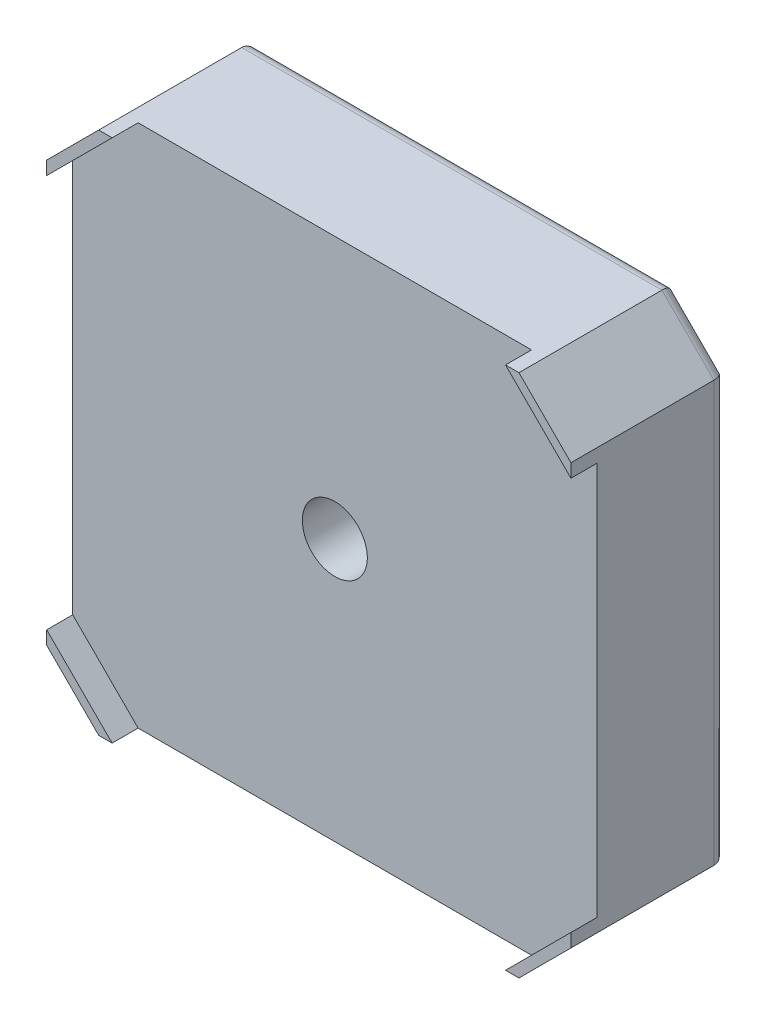
SolidWorks part; units mm, degrees
ref_plane "Front Plane" through (0, 0, 0) normal (0, 0, 1) x (1, 0, 0)
ref_plane "Top Plane" through (0, 0, 0) normal (0, 1, 0) x (1, 0, 0)
ref_plane "Right Plane" through (0, 0, 0) normal (1, 0, 0) x (0, 0, -1)
sketch "Sketch1" plane through (0, 0, 0) normal (0, 0, 1) x (1, 0, 0)
  line L0 (-48.5, 60.5) -> (-60.5, 48.5)
  line L1 (48.5, -60.5) -> (-48.5, -60.5)
  line L2 (60.5, -48.5) -> (60.5, 48.5)
  line L3 (48.5, 60.5) -> (-48.5, 60.5)
  line L4 (-60.5, -48.5) -> (-60.5, 48.5)
  line L5 (60.5, -60.5) -> (-60.5, 60.5) construction
  line L6 (60.5, 60.5) -> (-60.5, -60.5) construction
  line L7 (60.5, 48.5) -> (48.5, 60.5)
  line L8 (60.5, -48.5) -> (48.5, -60.5)
  line L9 (-48.5, -60.5) -> (-60.5, -48.5)
  point P0 (0, 0)
  dimension "D1" = 121
  dimension "D2" = 121
extrude "Boss-Extrude1" add sketch "Sketch1" along normal blind 36
sketch "Sketch2" plane through (0, 0, 36) normal (0, 0, 1) x (1, 0, 0)
  line L0 (-42.45, 63.45) -> (-63.45, 42.45)
  line L1 (42.45, -63.45) -> (-42.45, -63.45)
  line L2 (63.45, -42.45) -> (63.45, 42.45)
  line L3 (42.45, 63.45) -> (-42.45, 63.45)
  line L4 (-63.45, -42.45) -> (-63.45, 42.45)
  line L5 (63.45, -63.45) -> (-63.45, 63.45) construction
  line L6 (63.45, 63.45) -> (-63.45, -63.45) construction
  line L7 (63.45, 42.45) -> (42.45, 63.45)
  line L8 (63.45, -42.45) -> (42.45, -63.45)
  line L9 (-42.45, -63.45) -> (-63.45, -42.45)
  point P0 (0, 0)
  dimension "D1" = 126.9
  dimension "D2" = 126.9
extrude "Cut-Extrude1" cut sketch "Sketch2" against normal blind 6
sketch "Sketch3" plane through (0, 0, 0) normal (0, 0, -1) x (-1, 0, 0)
  circle A0 centre (0, 0) radius 33
  dimension "D1" = 66
extrude "Boss-Extrude2" add sketch "Sketch3" along normal blind 6
sketch "Sketch4" plane through (0, 0, -6) normal (0, 0, -1) x (-1, 0, 0)
  circle A0 centre (0, 0) radius 16.5
  dimension "D1" = 33
extrude "Cut-Extrude2" cut sketch "Sketch4" against normal blind 21
sketch "Sketch5" plane through (0, 0, 15) normal (0, 0, -1) x (-1, 0, 0)
  circle A0 centre (0, 0) radius 7.5
  dimension "D1" = 15
extrude "Cut-Extrude3" cut sketch "Sketch5" against normal through all
fillet "Fillet1" radius 3 8 edges at (-54.5, 54.5, 0) (-54.5, -54.5, 0) (-60.5, 0, 0) (0, -60.5, 0) (54.5, -54.5, 0) (60.5, 0, 0) (54.5, 54.5, 0) (0, 60.5, 0)
fillet "Fillet2" radius 1.5 3 edges at (-33, 0, -6) (-16.5, 0, 15) (-16.5, 0, -6)
sketch "Sketch6" plane through (0, 0, 0) normal (0, 0, -1) x (-1, 0, 0)
  line L1 (46.5, -46.5) -> (-46.5, -46.5) construction
  line L2 (46.5, -46.5) -> (46.5, 46.5) construction
  line L3 (46.5, 46.5) -> (-46.5, 46.5) construction
  line L4 (-46.5, -46.5) -> (-46.5, 46.5) construction
  line L5 (46.5, -46.5) -> (-46.5, 46.5) construction
  line L6 (46.5, 46.5) -> (-46.5, -46.5) construction
  circle A0 centre (-46.5, 46.5) radius 4.5
  circle A1 centre (46.5, 46.5) radius 4.5
  circle A2 centre (46.5, -46.5) radius 4.5
  circle A3 centre (-46.5, -46.5) radius 4.5
  point P0 (0, 0)
  dimension "D1" = 9
  dimension "D2" = 93
extrude "Cut-Extrude4" cut sketch "Sketch6" against normal blind 9
fillet "Fillet3" radius 1.5 4 edges at (42, -46.5, 0) (-51, -46.5, 0) (-51, 46.5, 0) (42, 46.5, 0)
scale "Escala2" scale about centroid uniform scaling yes scale factor 0.5
